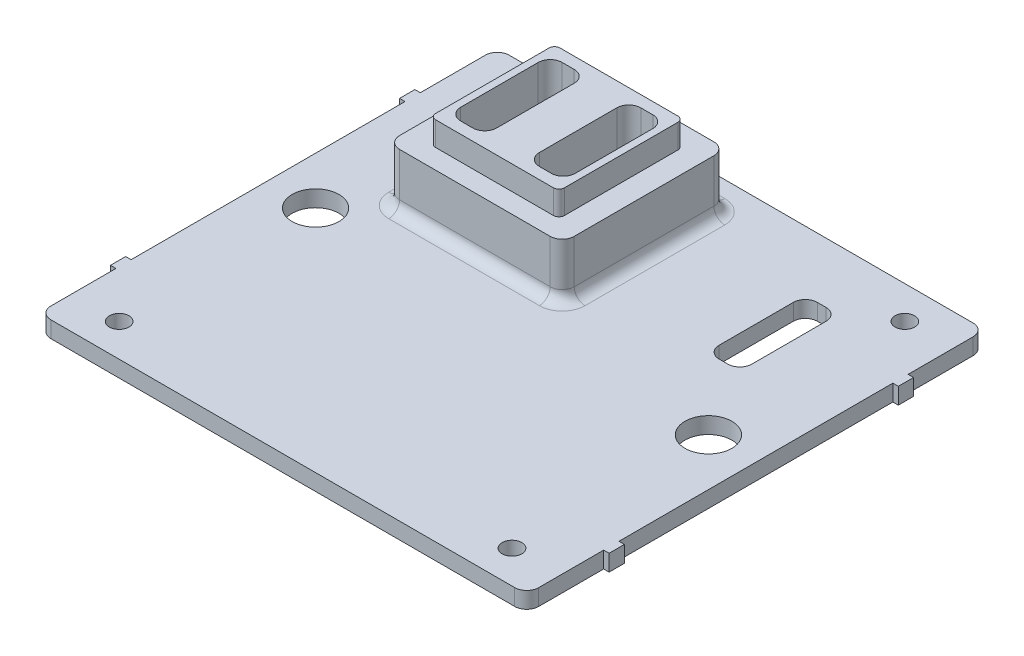
SolidWorks part; units mm, degrees
ref_plane "前视基准面" through (0, 0, 0) normal (0, 0, 1) x (1, 0, 0)
ref_plane "上视基准面" through (0, 0, 0) normal (0, 1, 0) x (1, 0, 0)
ref_plane "右视基准面" through (0, 0, 0) normal (1, 0, 0) x (0, 0, -1)
other "Configuration Table"
sketch "草图1" plane through (0, 0, 0) normal (0, 1, 0) x (1, 0, 0)
  line L0 (-22.35, -12.55) -> (-22.85, -12.55)
  line L5 (-22.35, 21) -> (22.35, 21)
  line L6 (-22.35, 21) -> (-22.35, 13.95)
  line L7 (-22.35, -21) -> (22.35, -21)
  line L8 (22.35, 21) -> (22.35, 13.95)
  line L9 (-22.35, 21) -> (22.35, -21) construction
  line L10 (-22.35, -21) -> (22.35, 21) construction
  line L11 (-22.85, -12.55) -> (-22.85, -13.95)
  line L12 (-22.85, -13.95) -> (-22.35, -13.95)
  line L13 (-22.35, 13.95) -> (-22.85, 13.95)
  line L14 (-22.85, 13.95) -> (-22.85, 12.55)
  line L15 (-22.85, 12.55) -> (-22.35, 12.55)
  line L16 (0, 0) -> (-22.5, 0) construction
  line L17 (0, 0) -> (0, 21) construction
  line L18 (-22.85, -13.25) -> (-22.35, -13.25) construction
  line L19 (-22.85, 13.25) -> (-22.35, 13.25) construction
  line L20 (22.85, -13.95) -> (22.35, -13.95)
  line L21 (22.85, -12.55) -> (22.85, -13.95)
  line L22 (22.35, -12.55) -> (22.85, -12.55)
  line L23 (22.85, 12.55) -> (22.35, 12.55)
  line L24 (22.85, 13.95) -> (22.85, 12.55)
  line L25 (22.35, 13.95) -> (22.85, 13.95)
  line L26 (-22.35, 13.25) -> (-22.35, 12.55) construction
  line L27 (-22.35, 12.55) -> (-22.35, -12.55)
  line L28 (-22.35, 13.95) -> (-22.35, 13.25) construction
  line L29 (-22.35, -13.25) -> (-22.35, -13.95) construction
  line L30 (-22.35, -13.95) -> (-22.35, -21)
  line L31 (-22.35, -12.55) -> (-22.35, -13.25) construction
  line L32 (22.35, -12.55) -> (22.35, -13.95) construction
  line L33 (22.35, -13.95) -> (22.35, -21)
  line L34 (22.35, 13.95) -> (22.35, 12.55) construction
  line L35 (22.35, 12.55) -> (22.35, -12.55)
  point P0 (0, 0)
  dimension "D1" = 42
  dimension "D2" = 44.7
  dimension "D3" = 0.5
  dimension "D4" = 0.5
  dimension "D5" = 1.4
  dimension "D6" = 1.4
  dimension "D7" = 26.5
extrude "凸台-拉伸1" add sketch "草图1" along normal blind 1.5
sketch "草图2" plane through (0, 1.5, 0) normal (0, 1, 0) x (1, 0, 0)
  line L0 (0, 0) -> (0, 9.3069) construction
  circle A0 centre (-18, 0) radius 2.15
  circle A1 centre (18, 0) radius 2.15
  circle A2 centre (-18, -18) radius 0.9
  circle A3 centre (-18, 18) radius 0.9
  circle A4 centre (18, -18) radius 0.9
  circle A5 centre (18, 18) radius 0.9
  dimension "D1" = 4.3
  dimension "D3" = 1.8
  dimension "D2" = 36
  dimension "D4" = 18
  dimension "D5" = 18
extrude "切除-拉伸1" cut sketch "草图2" against normal through all
sketch "草图3" plane through (0, 1.5, 0) normal (0, 1, 0) x (1, 0, 0)
  line L0 (22.35, 21) -> (-22.35, 21) construction
  line L1 (-13, 17) -> (-0.8, 17)
  line L2 (-13, 17) -> (-13, 5)
  line L3 (-13, 5) -> (-0.8, 5)
  line L4 (-0.8, 17) -> (-0.8, 5)
  line L5 (-13, 17) -> (-0.8, 5) construction
  line L6 (-13, 5) -> (-0.8, 17) construction
  line L9 (-21, -21) -> (21, -21) construction
  line L10 (-21, -21) -> (-21, 21) construction
  line L11 (-21, 21) -> (21, 21) construction
  line L12 (21, -21) -> (21, 21) construction
  line L13 (-21, -21) -> (21, 21) construction
  line L14 (-21, 21) -> (21, -21) construction
  point P0 (-6.9, 11)
  point P8 (0, 0)
  dimension "D1" = 12.2
  dimension "D2" = 12
  dimension "D3" = 4
  dimension "D4" = 42
  dimension "D5" = 8
extrude "凸台-拉伸2" add sketch "草图3" along normal blind 7.2
sketch "草图4" plane through (0, 1.5, 0) normal (0, 1, 0) x (1, 0, 0)
  line L0 (-6.9, 17) -> (-6.9, 11) construction
  line L1 (-14.9, 18.5) -> (1.1, 18.5)
  line L2 (-14.9, 18.5) -> (-14.9, 3.5)
  line L3 (-14.9, 3.5) -> (1.1, 3.5)
  line L4 (1.1, 18.5) -> (1.1, 3.5)
  line L5 (-14.9, 18.5) -> (1.1, 3.5) construction
  line L6 (-14.9, 3.5) -> (1.1, 18.5) construction
  line L7 (-0.8, 17) -> (-13, 17) construction
  line L8 (-13, 11) -> (-6.9, 11) construction
  line L9 (-13, 17) -> (-13, 5) construction
  point P0 (-6.9, 11)
  dimension "D1" = 16
  dimension "D2" = 15
extrude "凸台-拉伸3" add sketch "草图4" along normal up to surface (7.2 mm away) up to face at (-6.9, 8.7, -11)
sketch "草图5" plane through (0, 8.7, 0) normal (0, 1, 0) x (1, 0, 0)
  line L0 (-6.9, 17) -> (-6.9, 5) construction
  line L3 (-6.9, 11) -> (-13, 11) construction
  line L4 (-12.15, 15.65) -> (-8.85, 15.65)
  line L5 (-12.15, 15.65) -> (-12.15, 6.35)
  line L6 (-12.15, 6.35) -> (-8.85, 6.35)
  line L7 (-8.85, 15.65) -> (-8.85, 6.35)
  line L8 (-12.15, 15.65) -> (-8.85, 6.35) construction
  line L9 (-12.15, 6.35) -> (-8.85, 15.65) construction
  line L23 (-1.65, 6.35) -> (-4.95, 6.35)
  line L24 (-4.95, 15.65) -> (-4.95, 6.35)
  line L25 (-1.65, 15.65) -> (-4.95, 15.65)
  line L26 (-0.8, 17) -> (-13, 17)
  line L27 (-0.8, 5) -> (-0.8, 17)
  line L28 (-13, 5) -> (-0.8, 5)
  line L29 (-13, 17) -> (-13, 5)
  line L30 (-0.8, 17) -> (-13, 17) construction
  line L31 (-0.8, 5) -> (-0.8, 17) construction
  line L32 (-13, 5) -> (-0.8, 5) construction
  line L33 (-13, 17) -> (-13, 5) construction
  line L34 (-1.65, 15.65) -> (-1.65, 6.35)
  point P6 (-10.5, 11)
  dimension "D1" = 3.3
  dimension "D2" = 9.3
  dimension "D3" = 0
  dimension "D4" = 3.6
extrude "切除-拉伸2" cut sketch "草图5" against normal through all
sketch "草图6" plane through (0, 0, 0) normal (0, -1, 0) x (1, 0, 0)
  line L0 (-10.5, -6.35) -> (-10.5, -15.65) construction
  line L1 (-12.15, -6.35) -> (-8.85, -6.35) construction
  line L2 (-8.85, -15.65) -> (-12.15, -15.65) construction
  line L3 (-13, -11) -> (-0.8, -11) construction
  line L4 (-13, -17) -> (-0.8, -17)
  line L5 (-0.8, -17) -> (-0.8, -5)
  line L6 (-0.8, -5) -> (-13, -5)
  line L7 (-13, -5) -> (-13, -17)
  line L12 (-13, -17) -> (-0.8, -17) construction
  line L13 (-0.8, -17) -> (-0.8, -5) construction
  line L14 (-0.8, -5) -> (-13, -5) construction
  line L15 (-13, -5) -> (-13, -17) construction
  line L16 (-6.9, -11) -> (-6.9, -5) construction
  line L17 (-13.2, -4.8) -> (-7.8, -4.8)
  line L18 (-13.2, -4.8) -> (-13.2, -17.2)
  line L19 (-13.2, -17.2) -> (-7.8, -17.2)
  line L20 (-7.8, -4.8) -> (-7.8, -17.2)
  line L21 (-13.2, -4.8) -> (-7.8, -17.2) construction
  line L22 (-13.2, -17.2) -> (-7.8, -4.8) construction
  line L23 (-0.6, -17.2) -> (-6, -17.2)
  line L24 (-6, -4.8) -> (-6, -17.2)
  line L25 (-0.6, -4.8) -> (-6, -4.8)
  line L26 (-0.6, -4.8) -> (-0.6, -17.2)
  point P12 (-10.5, -11)
  dimension "D2" = 12.4
  dimension "D3" = 5.4
  dimension "D1" = 0
extrude "切除-拉伸3" cut sketch "草图6" against normal blind 2.7
sketch "草图7" plane through (0, 0, 0) normal (0, -1, 0) x (1, 0, 0)
  line L1 (11.38, -6.5) -> (14.38, -6.5)
  line L2 (11.38, -6.5) -> (11.38, -15.5)
  line L3 (11.38, -15.5) -> (14.38, -15.5)
  line L4 (14.38, -6.5) -> (14.38, -15.5)
  line L5 (11.38, -6.5) -> (14.38, -15.5) construction
  line L6 (11.38, -15.5) -> (14.38, -6.5) construction
  line L7 (-21, -21) -> (21, -21) construction
  line L8 (-21, -21) -> (-21, 21) construction
  line L9 (-21, 21) -> (21, 21) construction
  line L10 (21, -21) -> (21, 21) construction
  line L11 (-21, -21) -> (21, 21) construction
  line L12 (-21, 21) -> (21, -21) construction
  point P0 (12.88, -11)
  point P5 (0, 0)
  dimension "D1" = 42
  dimension "D2" = 8.12
  dimension "D3" = 10
  dimension "D4" = 3
  dimension "D5" = 9
extrude "切除-拉伸4" cut sketch "草图7" against normal through all
sketch "草图8" plane through (0, 8.7, 0) normal (0, 1, 0) x (1, 0, 0)
  line L0 (-13, 11) -> (-0.8, 11) construction
  line L5 (-14.9, 18.5) -> (1.1, 18.5)
  line L6 (-14.9, 18.5) -> (-14.9, 3.5)
  line L7 (-14.9, 3.5) -> (1.1, 3.5)
  line L8 (-0.8, 17) -> (-13, 17)
  line L9 (-0.8, 5) -> (-0.8, 17)
  line L10 (-13, 5) -> (-0.8, 5)
  line L11 (-13, 17) -> (-13, 5)
  line L12 (-0.8, 17) -> (-13, 17) construction
  line L13 (-0.8, 5) -> (-0.8, 17) construction
  line L14 (-13, 5) -> (-0.8, 5) construction
  line L15 (-13, 17) -> (-13, 5) construction
  line L16 (1.1, 18.5) -> (1.1, 3.5)
  line L17 (-12.8, 16.7) -> (-1, 16.7)
  line L18 (-12.8, 16.7) -> (-12.8, 5.3)
  line L19 (-12.8, 5.3) -> (-1, 5.3)
  line L20 (-1, 16.7) -> (-1, 5.3)
  line L21 (-12.8, 16.7) -> (-1, 5.3) construction
  line L22 (-12.8, 5.3) -> (-1, 16.7) construction
  line L23 (-6.9, 17) -> (-6.9, 5.3) construction
  point P8 (-6.9, 11)
  dimension "D1" = 0
  dimension "D2" = 11.8
  dimension "D3" = 11.4
extrude "切除-拉伸5" cut sketch "草图8" against normal blind 2.2
fillet "圆角1" radius 1.1 20 edges at (-1.65, 5.7, -6.35) (-4.95, 5.7, -6.35) (-1.65, 5.7, -15.65) (-4.95, 5.7, -15.65) (-8.85, 5.7, -6.35) (-12.15, 5.7, -6.35) (-8.85, 5.7, -15.65) (-12.15, 5.7, -15.65) (-14.9, 4, -3.5) (-14.9, 4, -18.5) (1.1, 4, -18.5) (1.1, 4, -3.5) (-22.35, 0.75, -21) (22.35, 0.75, -21) (22.35, 0.75, 21) (-22.35, 0.75, 21) (11.38, 0.75, -15.5) (14.38, 0.75, -15.5) (11.38, 0.75, -6.5) (14.38, 0.75, -6.5)
fillet "圆角2" radius 0.5 4 edges at (-1, 7.6, -16.7) (-12.8, 7.6, -16.7) (-1, 7.6, -5.3) (-12.8, 7.6, -5.3)
fillet "圆角3" radius 1 8 edges at (-14.5778, 1.5, -3.8222) (-14.9, 1.5, -11) (-14.5778, 1.5, -18.1778) (-6.9, 1.5, -18.5) (0.7778, 1.5, -18.1778) (1.1, 1.5, -11) (0.7778, 1.5, -3.8222) (-6.9, 1.5, -3.5)
chamfer "倒角1" distance 0.4 angle 45 8 edges at (-7.8, 1.35, -17.2) (-13.2, 1.35, -17.2) (-7.8, 1.35, -4.8) (-13.2, 1.35, -4.8) (-6, 1.35, -4.8) (-0.6, 1.35, -4.8) (-0.6, 1.35, -17.2) (-6, 1.35, -17.2)
